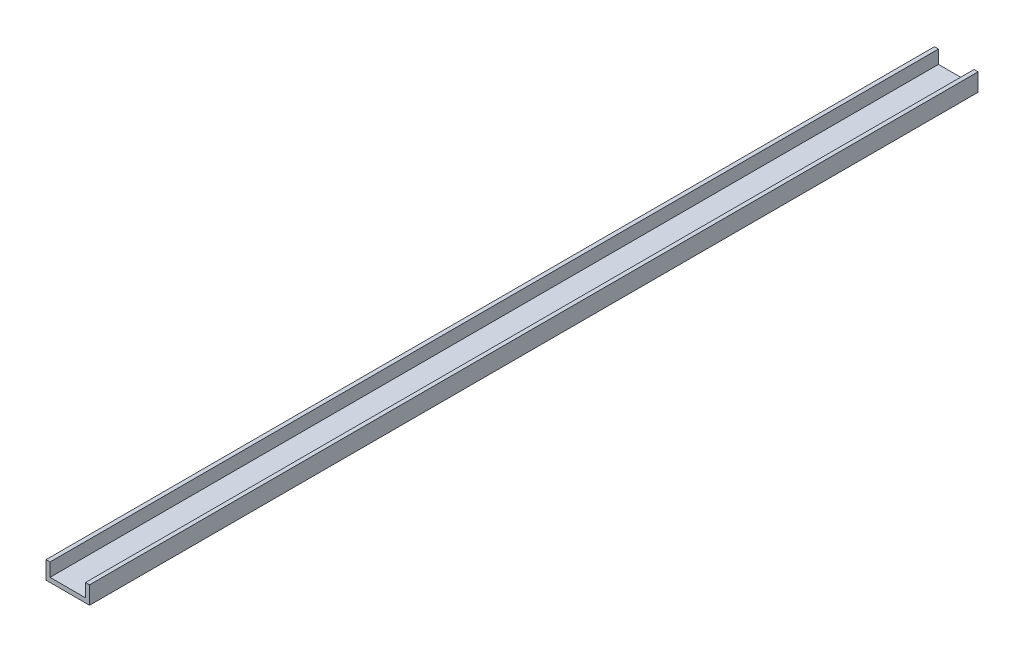
SolidWorks part; units mm, degrees
ref_plane "Front Plane" through (0, 0, 0) normal (0, 0, 1) x (1, 0, 0)
ref_plane "Top Plane" through (0, 0, 0) normal (0, 1, 0) x (1, 0, 0)
ref_plane "Right Plane" through (0, 0, 0) normal (1, 0, 0) x (0, 0, -1)
sketch "Sketch1" plane through (0, 0, 0) normal (0, 0, 1) x (1, 0, 0)
  line L0 (-41.526, 0) -> (-1.526, 0)
  line L1 (-1.526, 0) -> (-1.526, 15)
  line L2 (-1.526, 15) -> (2.974, 15)
  line L3 (2.974, 15) -> (2.974, -5)
  line L4 (2.974, -5) -> (-46.026, -5)
  line L5 (-46.026, -5) -> (-46.026, 15)
  line L6 (-46.026, 15) -> (-41.526, 15)
  line L7 (-41.526, 15) -> (-41.526, 0)
  dimension "D1" = 40
  dimension "D2" = 15
  dimension "D3" = 15
  dimension "D4" = 20
  dimension "D5" = 4.5
  dimension "D6" = 4.5
  dimension "D7" = 49
extrude "Boss-Extrude1" add sketch "Sketch1" along normal blind 1000
